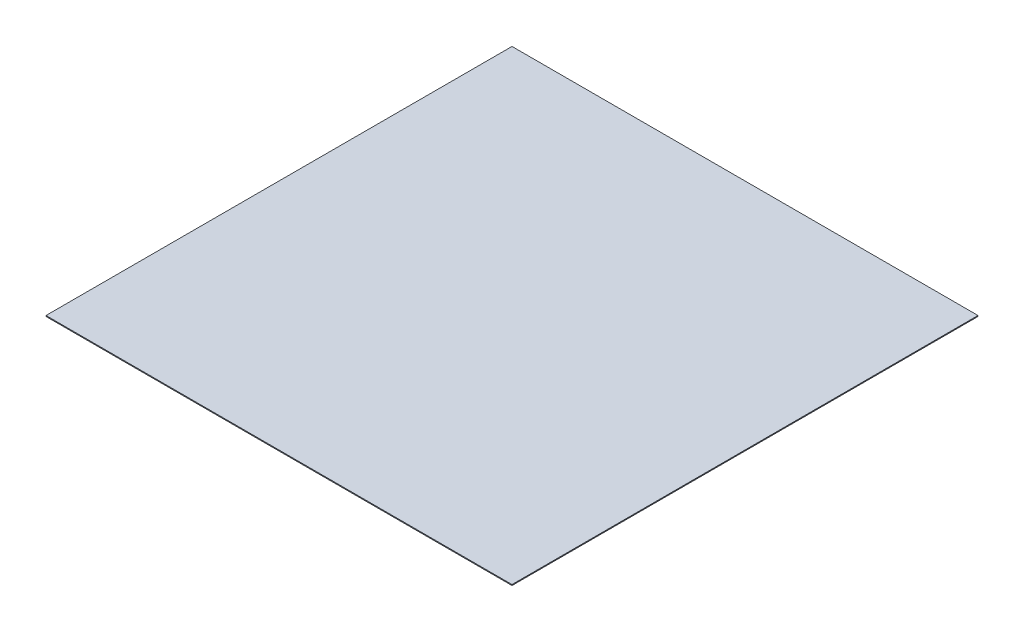
SolidWorks part; units mm, degrees
ref_plane "Front Plane" through (0, 0, 0) normal (0, 0, 1) x (1, 0, 0)
ref_plane "Top Plane" through (0, 0, 0) normal (0, 1, 0) x (1, 0, 0)
ref_plane "Right Plane" through (0, 0, 0) normal (1, 0, 0) x (0, 0, -1)
sketch "Sketch1" plane through (0, 0, 0) normal (0, 1, 0) x (1, 0, 0)
  line L1 (-26, 26) -> (26, 26)
  line L2 (-26, 26) -> (-26, -26)
  line L3 (-26, -26) -> (26, -26)
  line L4 (26, 26) -> (26, -26)
  line L5 (-26, 26) -> (26, -26) construction
  line L6 (-26, -26) -> (26, 26) construction
  point P0 (0, 0)
  dimension "D1" = 52
extrude "Boss-Extrude1" add sketch "Sketch1" along normal blind 0.1
